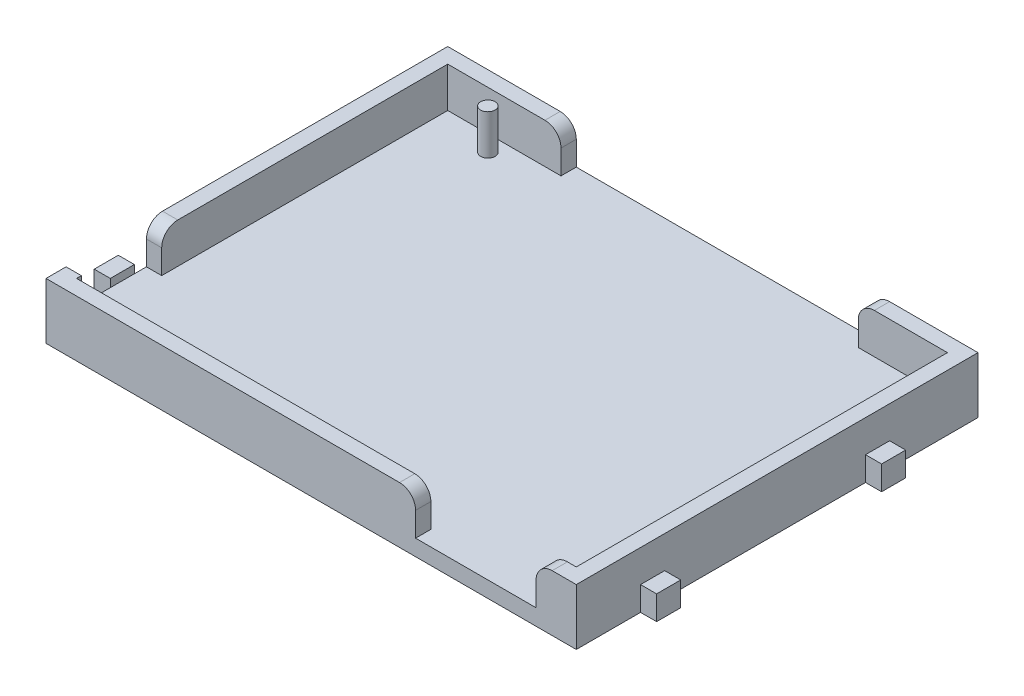
SolidWorks part; units mm, degrees
ref_plane "前视基准面" through (0, 0, 0) normal (0, 0, 1) x (1, 0, 0)
ref_plane "上视基准面" through (0, 0, 0) normal (0, 1, 0) x (1, 0, 0)
ref_plane "右视基准面" through (0, 0, 0) normal (1, 0, 0) x (0, 0, -1)
other "Configuration Table"
sketch "草图2" plane through (0, 0, 0) normal (0, 1, 0) x (1, 0, 0)
  line L1 (-33, 25) -> (33, 25)
  line L2 (-33, 25) -> (-33, -25)
  line L3 (-33, -25) -> (33, -25)
  line L4 (33, 25) -> (33, -25)
  line L5 (-33, 25) -> (33, -25) construction
  line L6 (-33, -25) -> (33, 25) construction
  point P0 (0, 0)
  dimension "D1" = 50
  dimension "D2" = 66
extrude "凸台-拉伸1" add sketch "草图2" along normal blind 2
sketch "草图3" plane through (0, 2, 0) normal (0, 1, 0) x (1, 0, 0)
  line L1 (-31.1, 23.1) -> (31.1, 23.1)
  line L2 (-31.1, 23.1) -> (-31.1, -23.1)
  line L3 (-31.1, -23.1) -> (31.1, -23.1)
  line L4 (31.1, 23.1) -> (31.1, -23.1)
  line L5 (-31.1, 23.1) -> (31.1, -23.1) construction
  line L6 (-31.1, -23.1) -> (31.1, 23.1) construction
  line L26 (33, -25) -> (33, 25)
  line L27 (33, 25) -> (-33, 25)
  line L28 (-33, 25) -> (-33, -25)
  line L29 (-33, -25) -> (33, -25)
  line L30 (33, -25) -> (33, 25)
  line L31 (33, 25) -> (-33, 25)
  line L32 (-33, 25) -> (-33, -25)
  line L33 (-33, -25) -> (33, -25)
  point P0 (0, 0)
  dimension "D1" = 46.2
  dimension "D2" = 62.2
  dimension "D3" = 0
extrude "凸台-拉伸2" add sketch "草图3" along normal blind 5
sketch "草图4" plane through (0, 7, 0) normal (0, 1, 0) x (1, 0, 0)
  line L0 (33, -25) -> (33, 25) construction
  line L1 (-17, 22.0385) -> (20, 22.0385)
  line L2 (-17, 22.0385) -> (-17, 28.2797)
  line L3 (-17, 28.2797) -> (20, 28.2797)
  line L4 (20, 22.0385) -> (20, 28.2797)
  line L5 (-33, 25) -> (-33, -25) construction
  dimension "D1" = 13
  dimension "D2" = 16
extrude "切除-拉伸1" cut sketch "草图4" against normal blind 5
sketch "草图5" plane through (0, 2, 0) normal (0, 1, 0) x (1, 0, 0)
  line L0 (-31.1, 23.1) -> (-31.1, -23.1) construction
  line L1 (-17, 23.1) -> (-31.1, 23.1) construction
  circle A0 centre (-24.1, 21.1) radius 0.9
  dimension "D3" = 1.8
  dimension "D1" = 7
  dimension "D2" = 2
extrude "凸台-拉伸3" add sketch "草图5" along normal blind 5
sketch "草图6" plane through (-33, 0, 0) normal (-1, 0, 0) x (0, 0, 1)
  line L0 (-25, 7) -> (25, 7) construction
  line L1 (12.5, 7) -> (22.5, 7)
  line L2 (12.5, 7) -> (12.5, 2)
  line L3 (12.5, 2) -> (22.5, 2)
  line L4 (22.5, 7) -> (22.5, 2)
  line L5 (-25, 0) -> (25, 0) construction
  line L6 (25, 7) -> (25, 0) construction
  dimension "D1" = 2
  dimension "D2" = 2.5
  dimension "D3" = 10
extrude "切除-拉伸2" cut sketch "草图6" against normal blind 5
sketch "草图7" plane through (0, 0, 25) normal (0, 0, 1) x (1, 0, 0)
  line L0 (-33, 7) -> (33, 7) construction
  line L1 (13, 7) -> (28, 7)
  line L2 (13, 7) -> (13, 2)
  line L3 (13, 2) -> (28, 2)
  line L4 (28, 7) -> (28, 2)
  line L5 (33, 7) -> (33, 0) construction
  line L6 (-33, 0) -> (33, 0) construction
  dimension "D1" = 5
  dimension "D2" = 15
  dimension "D3" = 2
extrude "切除-拉伸3" cut sketch "草图7" against normal blind 5
fillet "圆角1" radius 2 5 edges at (-32.05, 7, 12.5) (28, 7, 24.05) (13, 7, 24.05) (20, 7, -24.05) (-17, 7, -24.05)
sketch "草图8" plane through (33, 0, 0) normal (1, 0, 0) x (0, 0, -1)
  line L0 (-25, 0) -> (25, 0) construction
  line L1 (-17, 0) -> (-14, 0)
  line L2 (-17, 0) -> (-17, 3)
  line L3 (-17, 3) -> (-14, 3)
  line L4 (-14, 0) -> (-14, 3)
  line L5 (-25, 7) -> (-25, 0) construction
  line L7 (11, 0) -> (14, 0)
  line L8 (11, 0) -> (11, 3)
  line L9 (11, 3) -> (14, 3)
  line L10 (14, 0) -> (14, 3)
  dimension "D1" = 3
  dimension "D2" = 3
  dimension "D3" = 8
  dimension "D4" = 3
  dimension "D5" = 3
  dimension "D6" = 25
extrude "凸台-拉伸4" add sketch "草图8" along normal blind 2
mirror "镜向1" about plane through (0, 0, 0) normal (1, 0, 0) of "凸台-拉伸4"
